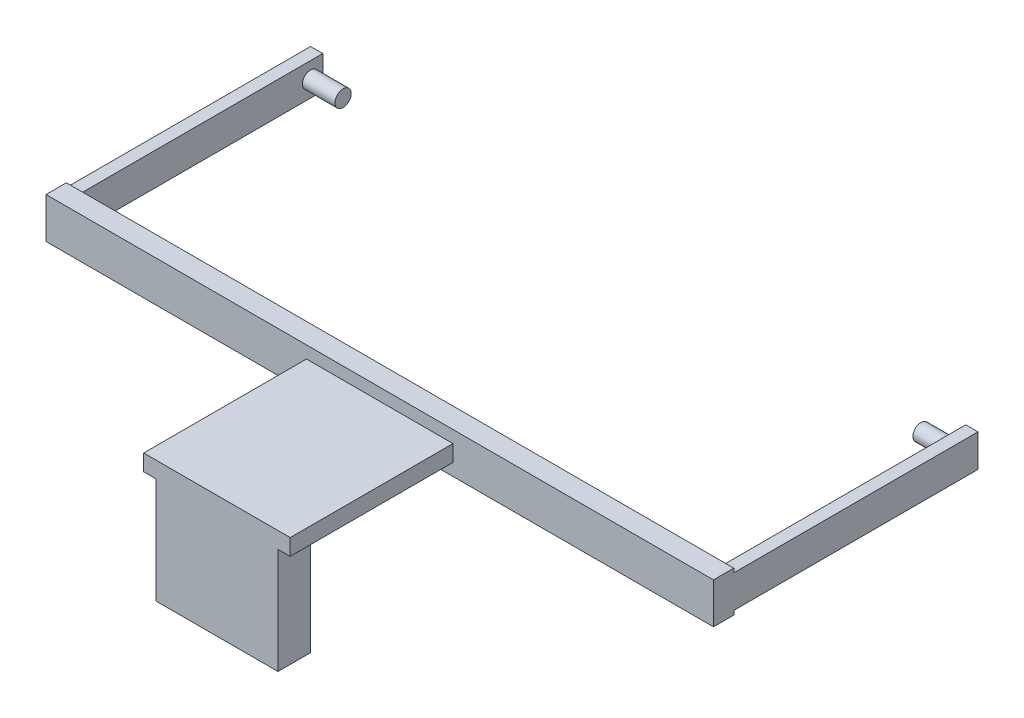
SolidWorks part; units mm, degrees
ref_plane "前视基准面" through (0, 0, 0) normal (0, 0, 1) x (1, 0, 0)
ref_plane "上视基准面" through (0, 0, 0) normal (0, 1, 0) x (1, 0, 0)
ref_plane "右视基准面" through (0, 0, 0) normal (1, 0, 0) x (0, 0, -1)
sketch "草图1" plane through (0, 0, 0) normal (0, 1, 0) x (1, 0, 0)
  line L1 (-82, 2.5) -> (82, 2.5)
  line L2 (-82, 2.5) -> (-82, -2.5)
  line L3 (-82, -2.5) -> (82, -2.5)
  line L4 (82, 2.5) -> (82, -2.5)
  line L5 (-82, 2.5) -> (82, -2.5) construction
  line L6 (-82, -2.5) -> (82, 2.5) construction
  point P0 (0, 0)
  dimension "D1" = 82
  dimension "D2" = 5
extrude "凸台-拉伸1" add sketch "草图1" along normal blind 10
sketch "草图2" plane through (0, 0, -2.5) normal (0, 0, -1) x (-1, 0, 0)
  line L0 (-82, 10) -> (-82, 0) construction
  line L1 (-82, 1) -> (-79, 1)
  line L2 (-82, 1) -> (-82, 9)
  line L3 (-82, 9) -> (-79, 9)
  line L4 (-79, 1) -> (-79, 9)
  line L5 (-82, 1) -> (-79, 9) construction
  line L6 (-82, 9) -> (-79, 1) construction
  line L7 (82, 10) -> (-82, 10) construction
  point P0 (-80.5, 5)
  point P7 (-80.5, 9)
  dimension "D1" = 3
  dimension "D2" = 0
  dimension "D3" = 8
  dimension "D4" = 1
extrude "凸台-拉伸2" add sketch "草图2" along normal blind 60
pattern_linear "阵列(线性)1" count 2 spacing 161 along (-1, 0, 0) of "凸台-拉伸2"
sketch "草图4" plane through (-79, 0, 0) normal (1, 0, 0) x (0, 0, -1)
  line L0 (62.5, 9) -> (2.5, 9) construction
  line L1 (62.5, 9) -> (62.5, 1) construction
  circle A0 centre (59.5, 5) radius 2
  point P6 (62.5, 5)
  dimension "D1" = 4
  dimension "D2" = 4
  dimension "D3" = 3
extrude "凸台-拉伸3" add sketch "草图4" along normal blind 8
sketch "草图5" plane through (79, 0, 0) normal (-1, 0, 0) x (0, 0, 1)
  line L0 (-62.5, 9) -> (-2.5, 9) construction
  line L1 (-62.5, 1) -> (-62.5, 9) construction
  circle A0 centre (-59.5, 5) radius 2
  dimension "D1" = 4
  dimension "D2" = 4
  dimension "D3" = 3
extrude "凸台-拉伸4" add sketch "草图5" along normal blind 8
sketch "草图6" plane through (0, 0, 2.5) normal (0, 0, 1) x (1, 0, 0)
  line L0 (-82, 0) -> (82, 0) construction
  line L1 (-18, 7) -> (18, 7)
  line L2 (-18, 7) -> (-18, 3)
  line L3 (-18, 3) -> (18, 3)
  line L4 (18, 7) -> (18, 3)
  line L5 (-18, 7) -> (18, 3) construction
  line L6 (-18, 3) -> (18, 7) construction
  line L7 (82, 10) -> (82, 0) construction
  point P0 (0, 5)
  dimension "D1" = 5
  dimension "D2" = 82
  dimension "D3" = 4
  dimension "D4" = 36
extrude "凸台-拉伸5" add sketch "草图6" along normal blind 40
sketch "草图7" plane through (0, 3, 0) normal (0, -1, 0) x (1, 0, 0)
  line L0 (-18, 42.5) -> (18, 42.5) construction
  line L1 (15, 34.5) -> (-15, 34.5)
  line L2 (15, 34.5) -> (15, 42.5)
  line L3 (15, 42.5) -> (-15, 42.5)
  line L4 (-15, 34.5) -> (-15, 42.5)
  line L5 (15, 34.5) -> (-15, 42.5) construction
  line L6 (15, 42.5) -> (-15, 34.5) construction
  line L7 (-18, 42.5) -> (-18, 2.5) construction
  point P0 (0, 38.5)
  dimension "D1" = 4
  dimension "D2" = 8
  dimension "D3" = 30
  dimension "D4" = 18
extrude "凸台-拉伸6" add sketch "草图7" along normal blind 26
